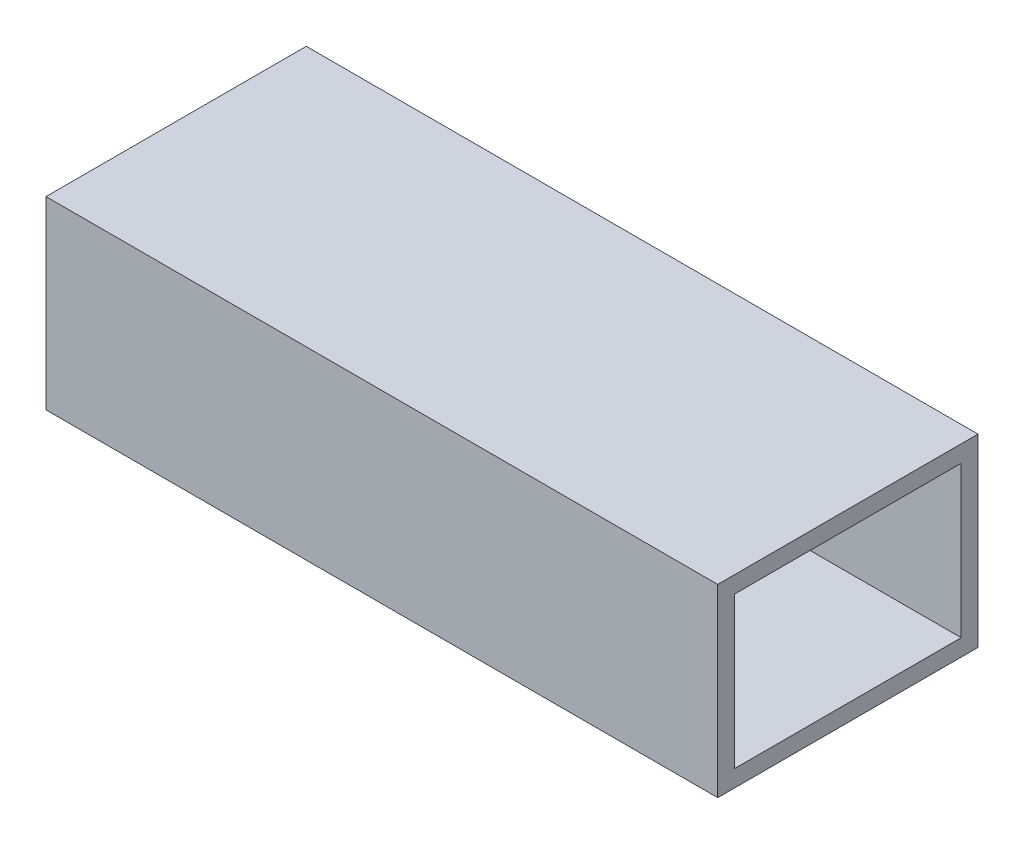
SolidWorks part; units mm, degrees
ref_plane "Front Plane" through (0, 0, 0) normal (0, 0, 1) x (1, 0, 0)
ref_plane "Top Plane" through (0, 0, 0) normal (0, 1, 0) x (1, 0, 0)
ref_plane "Right Plane" through (0, 0, 0) normal (1, 0, 0) x (0, 0, -1)
sketch "Sketch1" plane through (0, 0, 0) normal (0, 1, 0) x (1, 0, 0)
  circle A0 centre (0, 0) radius 107.95
sketch "Sketch2" plane through (0, 0, 0) normal (1, 0, 0) x (0, 0, -1)
  line L0 (-5.08, -5.08) -> (-5.08, 50.8)
  line L1 (0, 0) -> (68.58, 0)
  line L2 (0, 0) -> (0, 45.72)
  line L3 (0, 45.72) -> (68.58, 45.72)
  line L4 (68.58, 0) -> (68.58, 45.72)
  line L5 (-5.08, 50.8) -> (73.66, 50.8)
  line L6 (73.66, -5.08) -> (73.66, 50.8)
  line L7 (-5.08, -5.08) -> (73.66, -5.08)
  dimension "D1" = 5.08
extrude "Boss-Extrude1" add sketch "Sketch2" along normal blind 203.2
sketch "Sketch5" plane through (203.2, 0, 0) normal (1, 0, 0) x (0, 0, -1)
  line L1 (68.58, 45.72) -> (0, 45.72)
  line L2 (68.58, 45.72) -> (68.58, 0)
  line L3 (68.58, 0) -> (0, 0)
  line L4 (0, 45.72) -> (0, 0)
